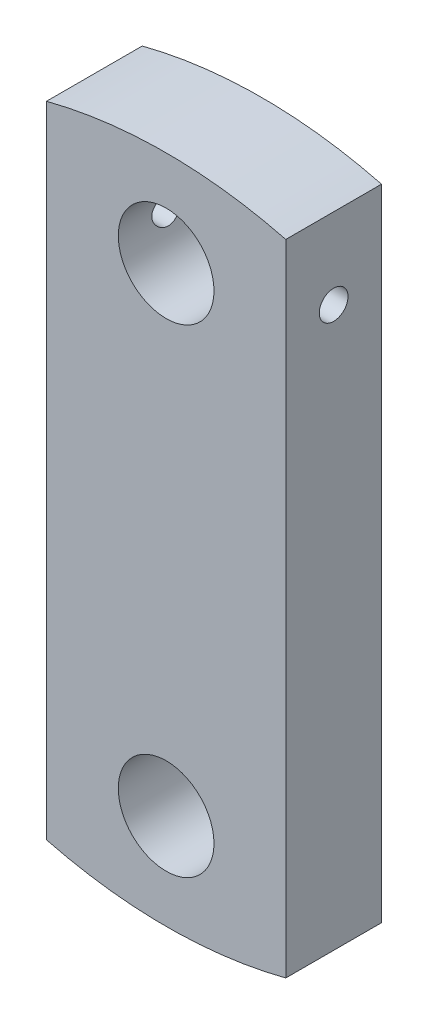
SolidWorks part; units mm, degrees
ref_plane "Front Plane" through (0, 0, 0) normal (0, 0, 1) x (1, 0, 0)
ref_plane "Top Plane" through (0, 0, 0) normal (0, 1, 0) x (1, 0, 0)
ref_plane "Right Plane" through (0, 0, 0) normal (1, 0, 0) x (0, 0, -1)
sketch "Sketch1" plane through (0, 0, 0) normal (0, 0, 1) x (1, 0, 0)
  line L0 (0, 35) -> (0, -35) construction
  line L2 (-12.5, -33.4123) -> (-12.5, 33.4123)
  line L4 (12.5, -33.4123) -> (12.5, 33.4123)
  line L7 (12.5, 0) -> (-12.5, 0) construction
  arc A0 (12.5, 33.4123) -> (-12.5, 33.4123) centre (0, -15) ccw
  arc A1 (12.5, -33.4123) -> (-12.5, -33.4123) centre (0, 15) cw
  circle A2 centre (0, -25) radius 5
  circle A3 centre (0, 25) radius 5
  point P0 (0, 0)
  dimension "D2" = 50
  dimension "D3" = 50
  dimension "D5" = 10
  dimension "D6" = 25
  dimension "D1" = 25
  dimension "D4" = 70
extrude "Corpo" add sketch "Sketch1" along normal blind 10
sketch "Sketch2" plane through (12.5, 0, 0) normal (1, 0, 0) x (0, 0, -1)
  line L0 (-5, 33.4123) -> (-5, -33.4123) construction
  line L1 (-10, 33.4123) -> (0, 33.4123) construction
  line L2 (-10, -33.4123) -> (0, -33.4123) construction
  circle A0 centre (-5, 25) radius 1.5
  point P8 (-5, 0)
  dimension "D1" = 3
  dimension "D2" = 25
extrude "Furo Ø3 Passante" cut sketch "Sketch2" against normal through all
